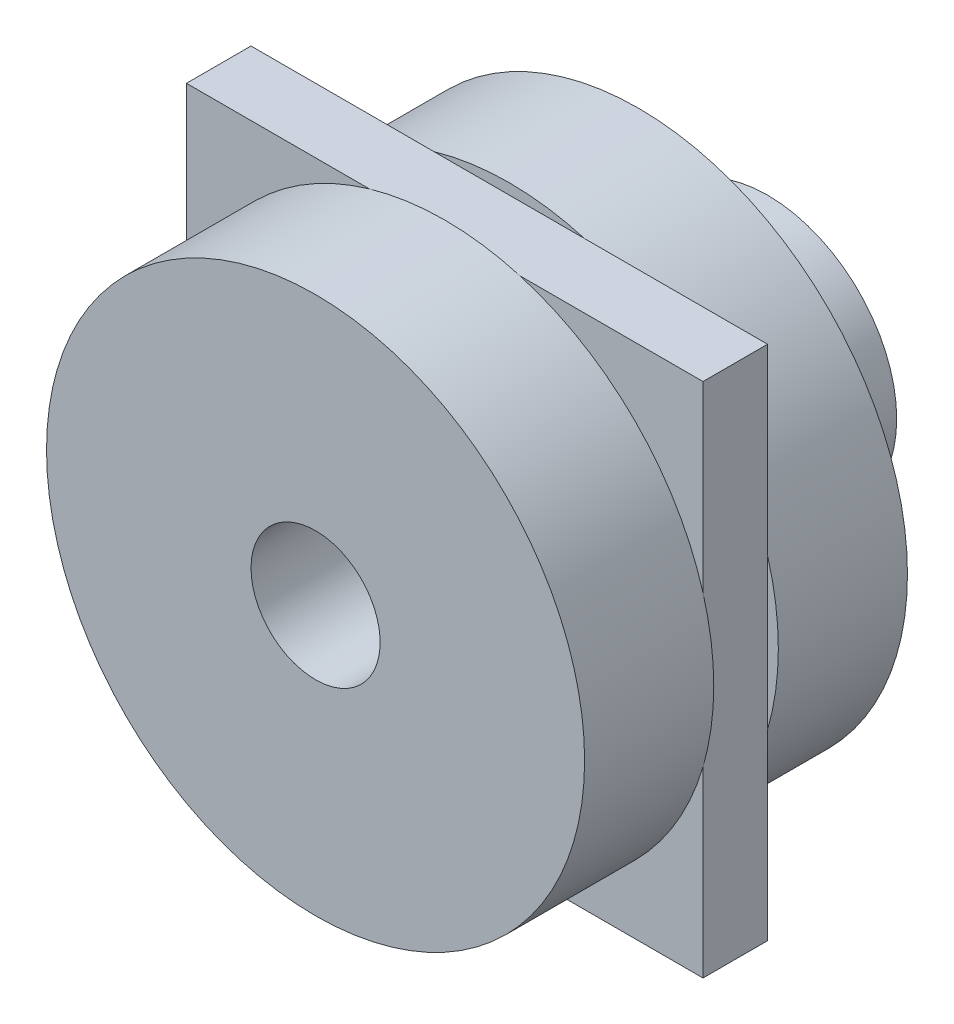
SolidWorks part; units mm, degrees
material "Настроенная пользователем пластмасса"
ref_plane "Спереди" through (0, 0, 0) normal (0, 0, 1) x (1, 0, 0)
ref_plane "Сверху" through (0, 0, 0) normal (0, 1, 0) x (1, 0, 0)
ref_plane "Справа" through (0, 0, 0) normal (1, 0, 0) x (0, 0, -1)
sketch "Эскиз1" plane through (0, 0, 0) normal (0, 0, 1) x (1, 0, 0)
  circle A0 centre (0, 0) radius 12.5
extrude "Бобышка-Вытянуть1" add sketch "Эскиз1" along normal blind 6
sketch "Эскиз2" plane through (0, 0, 0) normal (0, 0, -1) x (-1, 0, 0)
  circle A0 centre (0, 0) radius 6
extrude "Бобышка-Вытянуть2" add sketch "Эскиз2" along normal blind 6
sketch "Эскиз3" plane through (0, 0, 6) normal (0, 0, 1) x (1, 0, 0)
  line L1 (-12, -12) -> (12, -12)
  line L2 (-12, -12) -> (-12, 12)
  line L3 (-12, 12) -> (12, 12)
  line L4 (12, -12) -> (12, 12)
  line L5 (-12, -12) -> (12, 12) construction
  line L6 (-12, 12) -> (12, -12) construction
  point P2 (0, 0)
  dimension "D1" = 24
  dimension "D2" = 24
extrude "Бобышка-Вытянуть3" add sketch "Эскиз3" along normal blind 3
sketch "Эскиз4" plane through (0, 0, 9) normal (0, 0, 1) x (1, 0, 0)
  circle A0 centre (0, 0) radius 12.5
extrude "Бобышка-Вытянуть4" add sketch "Эскиз4" along normal blind 6
sketch "Вырез" plane through (0, 0, -6) normal (0, 0, -1) x (-1, 0, 0)
  circle A0 centre (0, 0) radius 3
extrude "Вырез-Вытянуть1" cut sketch "Вырез" against normal through all
